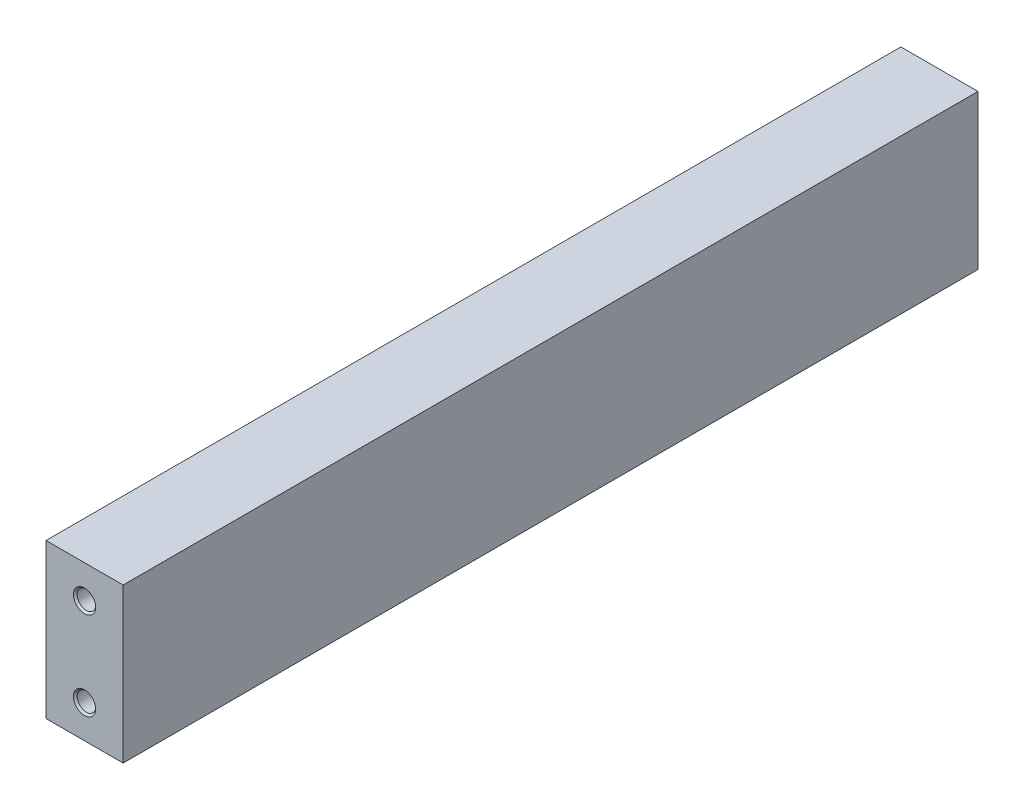
SolidWorks part; units mm, degrees
ref_plane "Ön Düzlem" through (0, 0, 0) normal (0, 0, 1) x (1, 0, 0)
ref_plane "Üst Düzlem" through (0, 0, 0) normal (0, 1, 0) x (1, 0, 0)
ref_plane "Sağ Düzlem" through (0, 0, 0) normal (1, 0, 0) x (0, 0, -1)
sketch "Sketch1" plane through (0, 0, 0) normal (0, 0, 1) x (1, 0, 0)
  line L1 (-8.75, -17.5) -> (8.75, -17.5)
  line L2 (-8.75, -17.5) -> (-8.75, 17.5)
  line L3 (-8.75, 17.5) -> (8.75, 17.5)
  line L4 (8.75, -17.5) -> (8.75, 17.5)
  line L5 (-8.75, -17.5) -> (8.75, 17.5) construction
  line L6 (-8.75, 17.5) -> (8.75, -17.5) construction
  point P0 (0, 0)
  dimension "D1" = 17.5
  dimension "D2" = 35
extrude "Boss-Extrude1" add sketch "Sketch1" along normal mid plane 194
sketch "Sketch2" plane through (0, 0, -97) normal (0, 0, -1) x (-1, 0, 0)
  line L0 (0, -10) -> (0, 10) construction
  point P4 (0, 0)
  dimension "D1" = 20
hole_wizard "M5 Tapped Hole1" positions "Sketch3" profile "Sketch5" tap size "M5" standard "ISO"
sketch "Sketch3" plane through (0, 0, -97) normal (0, 0, -1) x (-1, 0, 0)
  point P0 (0, 10)
  point P3 (0, -10)
cosmetic thread "Hole Thread1" parameters "D2"=5
cosmetic thread "Hole Thread2" parameters "D2"=5
sketch "Sketch5" plane through (0, 10, -97) normal (1, 0, 0) x (0, 1, 0)
  line L0 (0, 0) -> (0, 15.2618)
  line L1 (0, 15.2618) -> (2.1, 14)
  line L2 (2.1, 14) -> (2.1, 0.425)
  line L3 (2.1, 0.425) -> (2.525, 0)
  line L5 (2.525, 0) -> (0, 0)
  line L6 (-2.1, 0.425) -> (-2.525, 0) construction
  line L10 (0, 15.2618) -> (-2.1, 14) construction
  line L11 (0, -6.35) -> (0, 107.95) construction
  dimension "Tap Drill Dia." = 4.2
  dimension "Tap Drill Depth" = 14
  dimension "Near C'Sink Dia." = 5.05
  dimension "Near C'Sink Angle" = 90
  dimension "Drill Angle" = 118
mirror "Mirror1" about plane through (0, 0, 0) normal (0, 0, 1) of "M5 Tapped Hole1"
cosmetic thread "Hole Thread3" parameters "D2"=5
cosmetic thread "Hole Thread4" parameters "D2"=5
